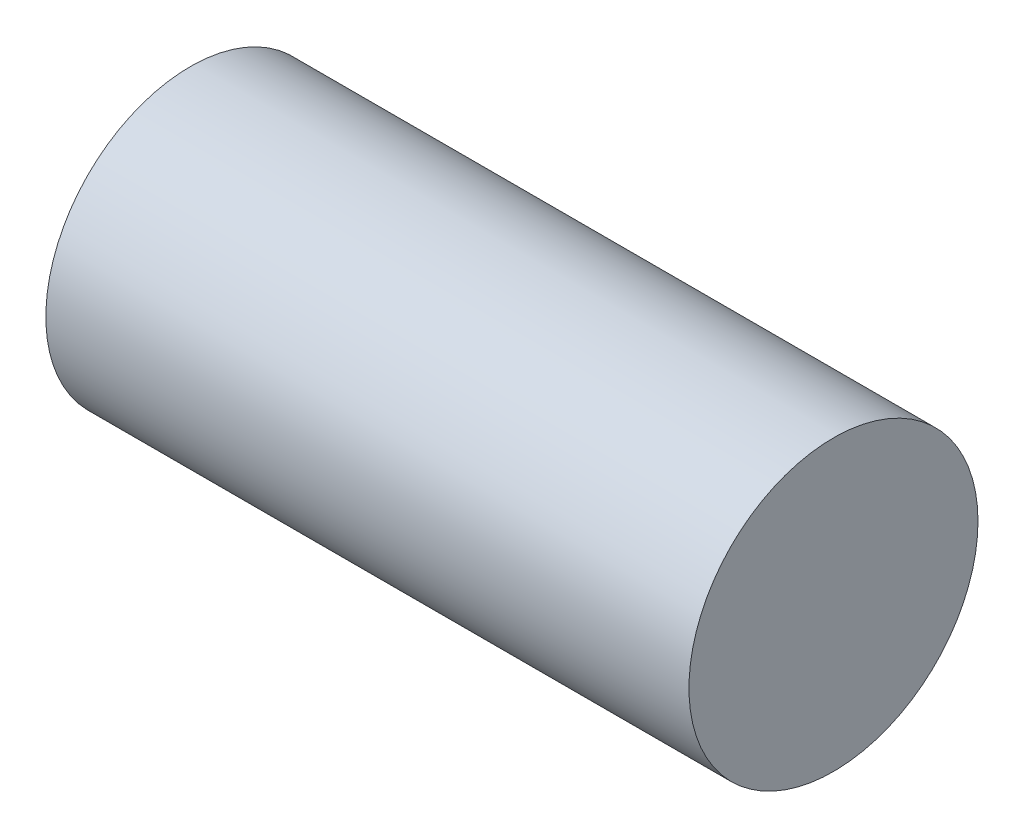
SolidWorks part; units mm, degrees
material "AISI 1045 钢，冷拔"
ref_plane "前视基准面" through (0, 0, 0) normal (0, 0, 1) x (1, 0, 0)
ref_plane "上视基准面" through (0, 0, 0) normal (0, 1, 0) x (1, 0, 0)
ref_plane "右视基准面" through (0, 0, 0) normal (1, 0, 0) x (0, 0, -1)
sketch "草图1" plane through (0, 0, 0) normal (1, 0, 0) x (0, 0, -1)
  circle A0 centre (0, 0) radius 20
extrude "凸台-拉伸1" add sketch "草图1" along normal blind 89
